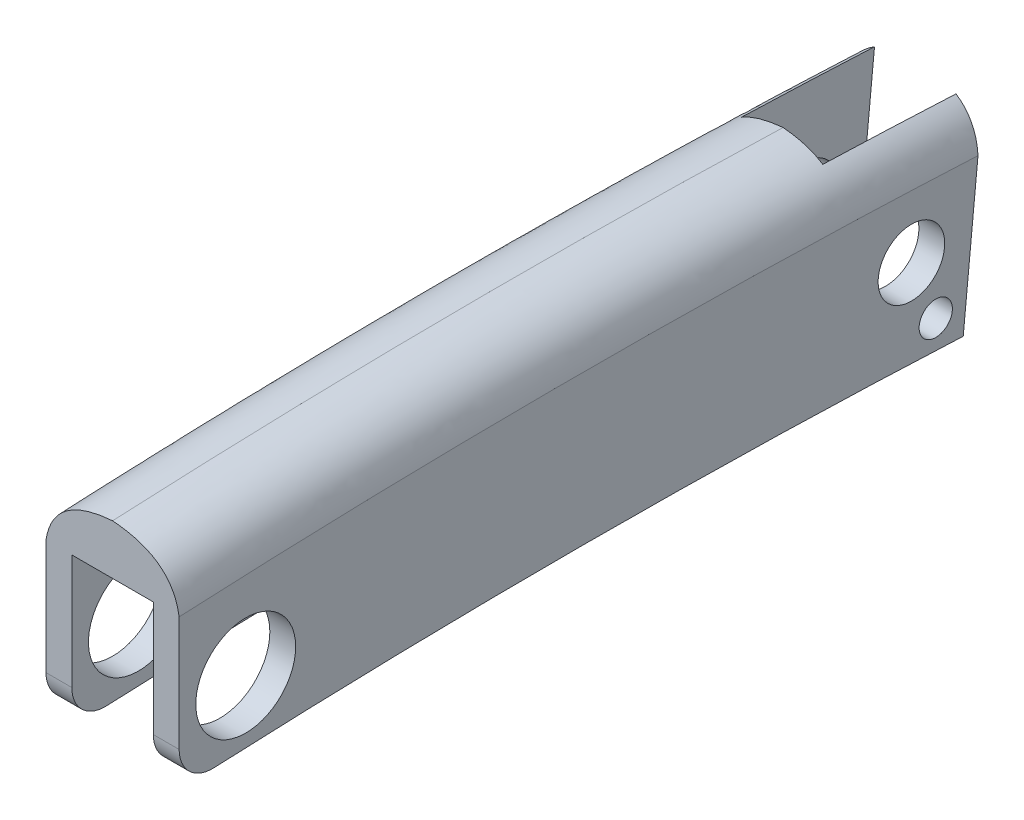
SolidWorks part; units mm, degrees
ref_plane "Front Plane" through (0, 0, 0) normal (0, 0, 1) x (1, 0, 0)
ref_plane "Top Plane" through (0, 0, 0) normal (0, 1, 0) x (1, 0, 0)
ref_plane "Right Plane" through (0, 0, 0) normal (1, 0, 0) x (0, 0, -1)
sketch "Sketch1" plane through (0, 0, 0) normal (0, 0, 1) x (1, 0, 0)
  line L0 (-1.2248, 0) -> (1.2248, 0)
  line L1 (1.2248, 0) -> (1.2248, -4.5)
  line L2 (1.2248, -4.5) -> (2, -4.5)
  line L3 (2, -4.5) -> (2, 0)
  line L4 (0, 0) -> (0, -1.6357) construction
  line L5 (0, 0) -> (0, 1.5) construction
  line L6 (-2, -4.5) -> (-2, 0)
  line L7 (-1.2248, -4.5) -> (-2, -4.5)
  line L8 (-1.2248, 0) -> (-1.2248, -4.5)
  spline S0 degree 2 poles (2, 0) (1.7892, 1.3633) (0, 1.5) knots 0 0 0 1 1 1
  spline S1 degree 2 poles (-2, 0) (-1.7892, 1.3633) (0, 1.5) knots 0 0 0 1 1 1
  point P4 (0, 0)
  point P12 (0, 1.4341)
  point P13 (0, 0)
  point P14 (1.8824, 0.4289)
  dimension "D1" = 4
  dimension "D2" = 6
  dimension "D3" = 1.5
sketch "Sketch2" plane through (0, 0, 0) normal (1, 0, 0) x (0, 0, -1)
  spline S0 degree 2 poles (0, 0) (12.0024, 0.5932) (24, 0) knots 0 0 0 1 1 1
  dimension "D1" = 24
sweep "Sweep1" add profiles "Sketch1" path "Sketch2"
sketch "Sketch4" plane through (2, 0, 0) normal (1, 0, 0) x (0, 0, -1)
  line L0 (2, -2.5242) -> (22, -1.7843) construction
  line L1 (0, -4.5) -> (0, 0) construction
  circle A0 centre (2, -2.5242) radius 1.5
  circle A1 centre (22, -1.7843) radius 1
  point P4 (18.1388, -0.8463)
  point P5 (1.7518, -2.5242)
  point P8 (22, -1.7843)
  dimension "D1" = 3
  dimension "D2" = 2
  dimension "D3" = 20
  dimension "D4" = 2
extrude "Cut-Extrude1" cut sketch "Sketch4" against normal blind 23
fillet "Fillet1" radius 1 2 edges at (-1.6124, -4.5, 0) (1.6124, -4.5, 0)
sketch "Sketch5" plane through (2, 0, 0) normal (1, 0, 0) x (0, 0, -1)
  circle A0 centre (22.7307, -3.5972) radius 0.5
  point P2 (22.7307, -3.5972)
  dimension "D1" = 1
extrude "Cut-Extrude2" cut sketch "Sketch5" against normal blind 23
sketch "Sketch6" plane through (0, -2.3553, -23.7666) normal (0, -0.0986, -0.9951) x (-1, 0, 0)
  line L4 (-1.2248, 0.6882) -> (1.2248, 0.6882)
  line L5 (-1.2248, 0.6882) -> (-1.2248, 5.7736)
  line L6 (1.2248, 0.6882) -> (1.2248, 5.7736)
  line L7 (-1.2248, 5.7736) -> (1.2248, 5.7736)
  line L8 (-1.2248, 0) -> (-1.2248, 2.3668) construction
  line L9 (1.2248, 2.3668) -> (1.2248, 0) construction
extrude "Cut-Extrude3" cut sketch "Sketch6" against normal blind 4
